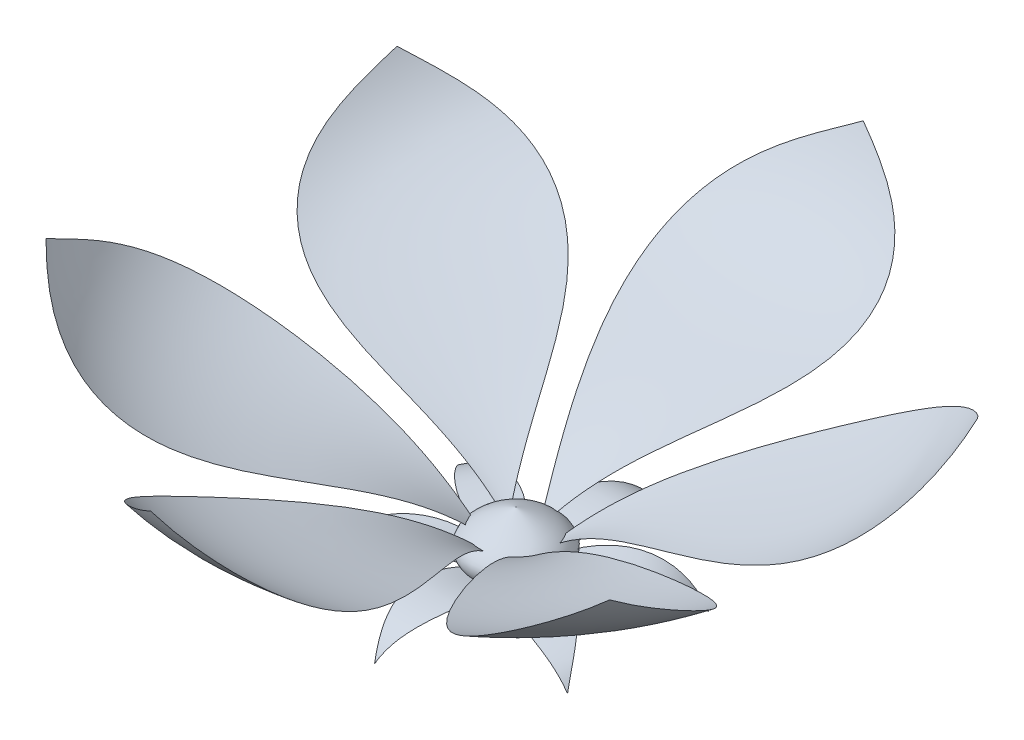
SolidWorks part; units mm, degrees
ref_plane "Front Plane" through (0, 0, 0) normal (0, 0, 1) x (1, 0, 0)
ref_plane "Top Plane" through (0, 0, 0) normal (0, 1, 0) x (1, 0, 0)
ref_plane "Right Plane" through (0, 0, 0) normal (1, 0, 0) x (0, 0, -1)
sketch "Sketch1" plane through (0, 0, 0) normal (0, 0, 1) x (1, 0, 0)
  line L0 (0, 0) -> (0, 41.9765) construction
  spline S0 degree 3 poles (0, 0) (-14.1786, 20.7973) (-47.9824, 7.5797) (-52.887, 41.9765) knots 0 0 0 0 1 1 1 1
surface "Surface-Revolve1" sketch "Sketch1" parameters "D1"=360
sketch "Sketch2" plane through (0, 0, 0) normal (1, 0, 0) x (0, 0, -1)
  line L0 (0, 0) -> (0, -12.3814) construction
  spline S0 degree 3 poles (0, 0) (-15.2151, 6.7786) (-23.7903, 2.4304) (-21.2778, -12.3814) knots 0 0 0 0 1 1 1 1
surface "Surface-Revolve2" sketch "Sketch2" parameters "D1"=360
sketch "Sketch3" plane through (0, 0, 0) normal (0, 1, 0) x (1, 0, 0)
  line L0 (0, 0) -> (0, 52.887) construction
  circle A0 centre (0, 0) radius 52.887 construction
  spline S0 degree 3 poles (0, 3.3171) (-8.0468, 19.1563) (-26.2021, 41.8779) (0, 49.8658) knots 0 0 0 0 1 1 1 1
  spline S1 degree 3 poles (0, 3.3171) (8.0468, 19.1563) (26.2021, 41.8779) (0, 49.8658) knots 0 0 0 0 1 1 1 1
surface "Surface-Trim1"
sketch "Sketch4" plane through (0, 0, 0) normal (0, 1, 0) x (1, 0, 0)
  line L0 (0, 0) -> (0, -40.5636) construction
  spline S0 degree 2 poles (0, 0) (-6.5037, -9.2768) (0, -20.2818) knots 0 0 0 1 1 1
  spline S1 degree 2 poles (0, 0) (6.5037, -9.2768) (0, -20.2818) knots 0 0 0 1 1 1
surface "Surface-Trim2"
sketch "Sketch5" plane through (0, 0, 0) normal (1, 0, 0) x (0, 0, -1)
  line L0 (0, -1.3055) -> (0, 8.2262)
  spline S0 degree 2 poles (0, 8.2262) (12.9, 3.4604) (0, -1.3055) knots 0 0 0 1 1 1
revolve "Revolve2" add sketch "Sketch5" angle 360 about L0
sketch "Sketch7" plane through (0, 0, 0) normal (1, 0, 0) x (0, 0, -1)
  line L0 (0, 0) -> (0, 24.4468) construction
pattern_circular "CirPattern1" count 6 every 59 about axis through (0, 0, 0) along (0, 1, 0) of bodies 103
pattern_circular "CirPattern2" count 6 over 360 about axis through (0, 0, 0) along (0, 1, 0) of bodies 104
sketch "Sketch9" plane through (0, 0, 0) normal (0, 1, 0) x (1, 0, 0)
  circle A0 centre (0, 0) radius 2
  dimension "D1" = 4
extrude "Boss-Extrude1" add sketch "Sketch9" against normal blind 2
